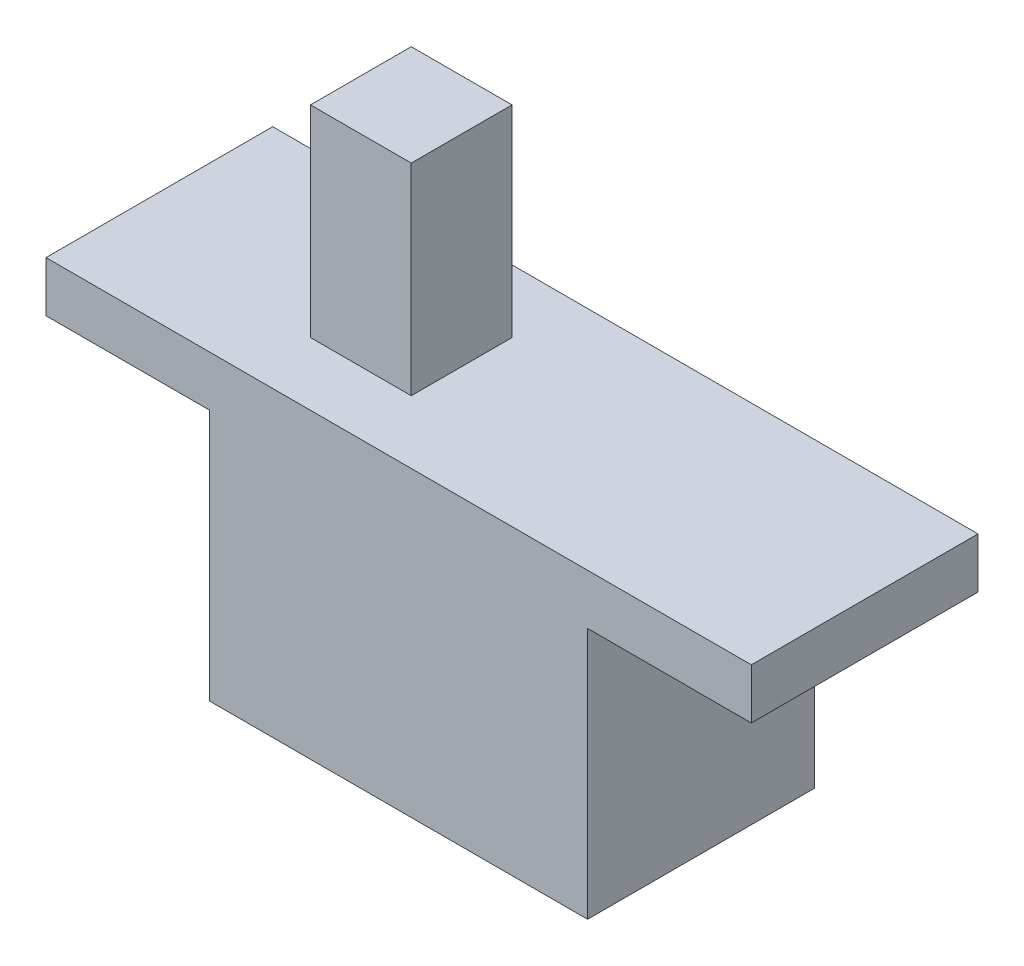
SolidWorks part; units mm, degrees
ref_plane "Alzado" through (0, 0, 0) normal (0, 0, 1) x (1, 0, 0)
ref_plane "Planta" through (0, 0, 0) normal (0, 1, 0) x (1, 0, 0)
ref_plane "Vista lateral" through (0, 0, 0) normal (1, 0, 0) x (0, 0, -1)
sketch "Croquis1" plane through (0, 0, 0) normal (0, 1, 0) x (1, 0, 0)
  line L1 (0, 0) -> (14, 0)
  line L2 (0, 0) -> (0, 4.5)
  line L3 (0, 4.5) -> (14, 4.5)
  line L4 (14, 0) -> (14, 4.5)
  dimension "D1" = 14
  dimension "D2" = 4.5
extrude "Saliente-Extruir1" add sketch "Croquis1" along normal blind 1
sketch "Croquis2" plane through (0, 1, 0) normal (0, 1, 0) x (1, 0, 0)
  line L0 (0, 0) -> (14, 0) construction
  line L1 (3.25, 0) -> (10.75, 0)
  line L2 (3.25, 0) -> (3.25, 4.5)
  line L3 (3.25, 4.5) -> (10.75, 4.5)
  line L4 (10.75, 0) -> (10.75, 4.5)
  line L5 (14, 4.5) -> (0, 4.5) construction
  point P8 (7, 0)
  point P9 (7, 0)
  dimension "D1" = 7.5
extrude "Saliente-Extruir2" add sketch "Croquis2" against normal blind 6
sketch "Croquis3" plane through (0, 1, 0) normal (0, 1, 0) x (1, 0, 0)
  line L0 (0, 2.25) -> (14, 2.25) construction
  line L1 (4, 3.25) -> (6, 3.25)
  line L2 (4, 3.25) -> (4, 1.25)
  line L3 (4, 1.25) -> (6, 1.25)
  line L4 (6, 3.25) -> (6, 1.25)
  line L5 (0, 4.5) -> (0, 0) construction
  line L6 (14, 0) -> (14, 4.5) construction
  point P10 (6, 2.25)
  dimension "D1" = 2
  dimension "D2" = 2
  dimension "D3" = 4
extrude "Saliente-Extruir3" add sketch "Croquis3" along normal blind 4
